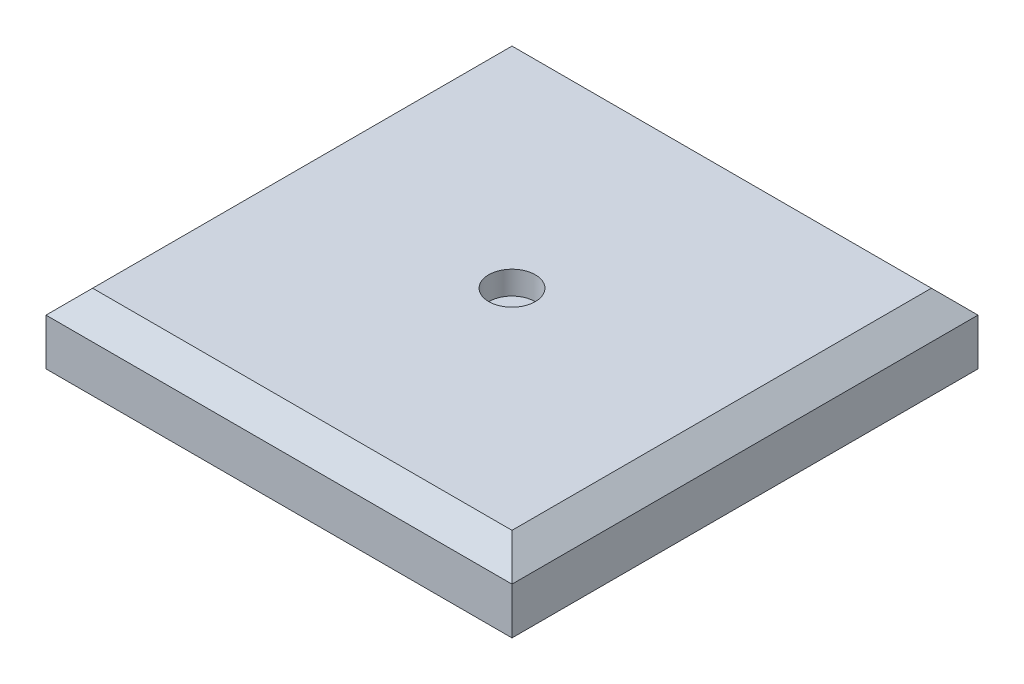
SolidWorks part; units mm, degrees
material "Hierro dúctil (SN)"
ref_plane "Alzado" through (0, 0, 0) normal (0, 0, 1) x (1, 0, 0)
ref_plane "Planta" through (0, 0, 0) normal (0, 1, 0) x (1, 0, 0)
ref_plane "Vista lateral" through (0, 0, 0) normal (1, 0, 0) x (0, 0, -1)
sketch "Croquis1" plane through (0, 0, 0) normal (0, 1, 0) x (1, 0, 0)
  line L1 (0, 0) -> (100, 0)
  line L2 (0, 0) -> (0, 100)
  line L3 (0, 100) -> (100, 100)
  line L4 (100, 0) -> (100, 100)
  dimension "D1" = 100
  dimension "D2" = 100
extrude "Saliente-Extruir1" add sketch "Croquis1" along normal blind 15
chamfer "Chaflán1" distance 5 angle 45 4 edges at (50, 15, -100) (100, 15, -50) (50, 15, 0) (0, 15, -50)
sketch "Croquis3" plane through (0, 15, 0) normal (0, 1, 0) x (1, 0, 0)
  line L0 (5, 95) -> (95, 5)
  line L1 (95, 5) -> (95, 95)
  line L2 (95, 95) -> (5, 5)
  circle A0 centre (50, 50) radius 5
extrude "Cortar-Extruir1" cut sketch "Croquis3" against normal blind 5 contours A0
